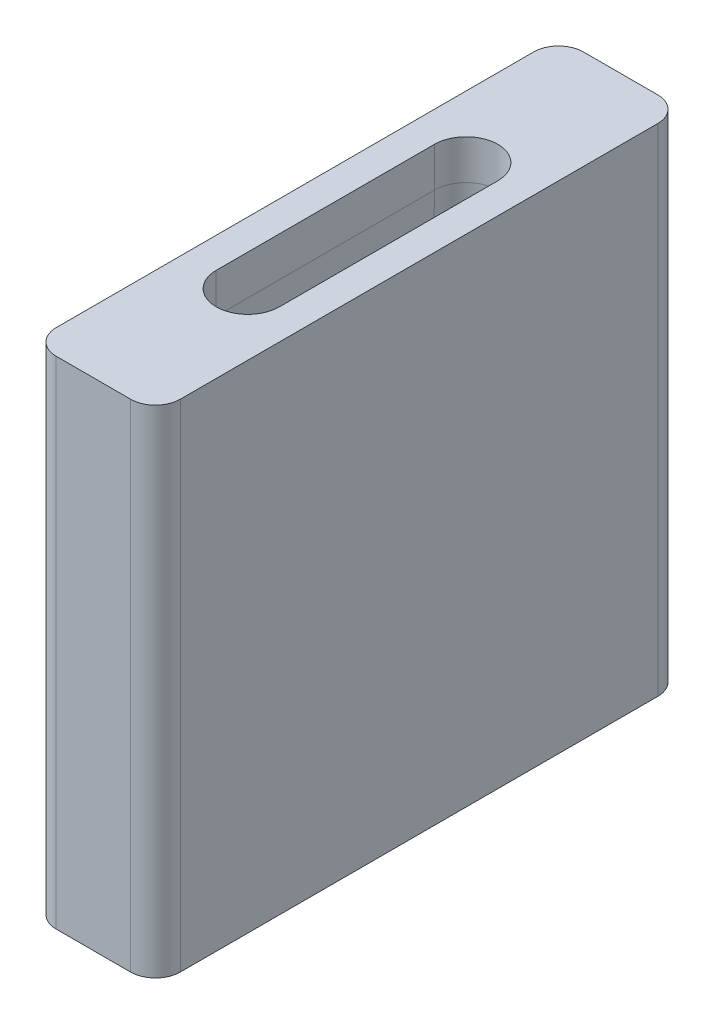
SolidWorks part; units mm, degrees
material "K110"
ref_plane "Front Plane" through (0, 0, 0) normal (0, 0, 1) x (1, 0, 0)
ref_plane "Top Plane" through (0, 0, 0) normal (0, 1, 0) x (1, 0, 0)
ref_plane "Right Plane" through (0, 0, 0) normal (1, 0, 0) x (0, 0, -1)
sketch "Sketch1" plane through (0, 0, 0) normal (0, 1, 0) x (1, 0, 0)
  line L3 (0, -3.5) -> (0, 3.5) construction
  line L4 (-2.62, -3.5) -> (-2.62, 3.5) construction
  line L5 (2.62, -3.5) -> (2.62, 3.5) construction
  line L6 (-3, -21.25) -> (3, -21.25)
  line L7 (-5, -19.25) -> (-5, 19.25)
  line L8 (-3, 21.25) -> (3, 21.25)
  line L9 (5, -19.25) -> (5, 19.25)
  line L10 (-5, -21.25) -> (5, 21.25) construction
  line L11 (-5, 21.25) -> (5, -21.25) construction
  arc A2 (-2.62, -3.5) -> (2.62, -3.5) centre (0, -3.5) ccw construction
  arc A3 (2.62, 3.5) -> (-2.62, 3.5) centre (0, 3.5) ccw construction
  arc A4 (-3, -21.25) -> (-5, -19.25) centre (-3, -19.25) cw
  arc A5 (3, -21.25) -> (5, -19.25) centre (3, -19.25) ccw
  arc A6 (3, 21.25) -> (5, 19.25) centre (3, 19.25) cw
  arc A7 (-5, 19.25) -> (-3, 21.25) centre (-3, 19.25) cw
  point P0 (0, 0)
  point P10 (0, 0)
  dimension "D1" = 7
  dimension "D3" = 2.62
  dimension "D5" = 2
  dimension "D2" = 42.5
  dimension "D4" = 10
extrude "Boss-Extrude1" add sketch "Sketch1" against normal blind 40
sketch "Sketch5" plane through (0, 0, 0) normal (0, 1, 0) x (1, 0, 0)
  line L0 (0, -8.8) -> (0, 8.8) construction
  line L1 (-2.55, -8.8) -> (-2.55, 8.8)
  line L2 (2.55, -8.8) -> (2.55, 8.8)
  arc A0 (-2.55, -8.8) -> (2.55, -8.8) centre (0, -8.8) ccw
  arc A1 (2.55, 8.8) -> (-2.55, 8.8) centre (0, 8.8) ccw
  point P4 (0, 0)
  dimension "D1" = 17.6
  dimension "D2" = 5.1
extrude "Cut-Extrude2" cut sketch "Sketch5" against normal up to next
sketch "Sketch7" plane through (0, 0, 0) normal (0, 0, 1) x (1, 0, 0)
  line L0 (2.55, -3.2) -> (3.1923, -40)
  line L1 (2.55, -40) -> (2.55, 0) construction
  line L2 (-3, -40) -> (3, -40) construction
  line L3 (3.1923, -40) -> (2.55, -40)
  line L4 (2.55, -40) -> (2.55, -3.2)
  line L5 (5, 0) -> (3, 0) construction
  dimension "D1" = 3.2
  dimension "D2" = 1
sketch "Sketch8" plane through (0, 0, 0) normal (0, 1, 0) x (1, 0, 0)
  line L0 (-2.55, 8.8) -> (-2.55, -8.8) construction
  line L1 (2.55, -8.8) -> (2.55, 8.8) construction
  line L2 (-2.55, 8.8) -> (-2.55, -8.8)
  line L3 (2.55, -8.8) -> (2.55, 8.8)
  arc A0 (2.55, 8.8) -> (-2.55, 8.8) centre (0, 8.8) ccw construction
  arc A1 (-2.55, -8.8) -> (2.55, -8.8) centre (0, -8.8) ccw construction
  arc A2 (2.55, 8.8) -> (-2.55, 8.8) centre (0, 8.8) ccw
  arc A3 (-2.55, -8.8) -> (2.55, -8.8) centre (0, -8.8) ccw
sweep "Cut-Sweep1" cut profiles "Sketch7" path "Sketch8"
hole_wizard "M6 Tapped Hole1" positions "Sketch11" profile "Sketch10" tap size "M6" standard "ISO"
sketch "Sketch11" plane through (0, -40, 0) normal (0, -1, 0) x (-1, 0, 0)
  line L0 (-3, 21.25) -> (3, 21.25) construction
  line L5 (3, -21.25) -> (-3, -21.25) construction
  line L6 (0, 21.25) -> (0, -21.25) construction
  point P0 (0, 16.25)
  point P2 (0, -16.25)
  dimension "D1" = 5
  dimension "D4" = 5
sketch "Sketch10" plane through (0, -40, -16.25) normal (1, 0, 0) x (0, 0, -1)
  line L0 (0, 0) -> (0, 18.5022)
  line L1 (0, 18.5022) -> (2.5, 17)
  line L2 (2.5, 17) -> (2.5, 0.525)
  line L3 (2.5, 0.525) -> (3.025, 0)
  line L5 (3.025, 0) -> (0, 0)
  line L6 (-2.5, 0.525) -> (-3.025, 0) construction
  line L10 (0, 18.5022) -> (-2.5, 17) construction
  line L11 (0, -6.35) -> (0, 107.95) construction
  dimension "Tap Drill Dia." = 5
  dimension "Tap Drill Depth" = 17
  dimension "Near C'Sink Dia." = 6.05
  dimension "Near C'Sink Angle" = 90
  dimension "Drill Angle" = 118
cosmetic thread "Hole Thread1"
cosmetic thread "Hole Thread2"
